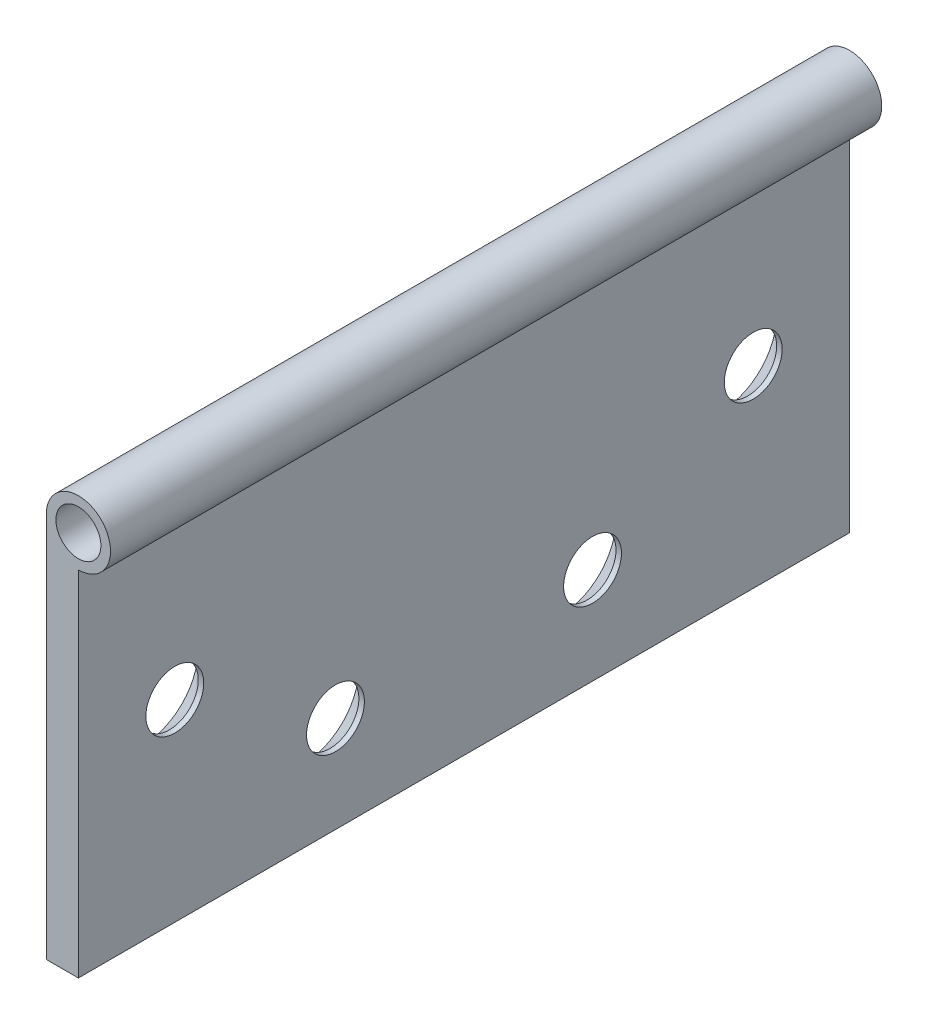
SolidWorks part; units mm, degrees
ref_plane "Спереди" through (0, 0, 0) normal (0, 0, 1) x (1, 0, 0)
ref_plane "Сверху" through (0, 0, 0) normal (0, 1, 0) x (1, 0, 0)
ref_plane "Справа" through (0, 0, 0) normal (1, 0, 0) x (0, 0, -1)
sketch "Эскиз1" plane through (0, 0, 0) normal (0, 0, 1) x (1, 0, 0)
  line L0 (0, 0) -> (0, 60)
  dimension "D1" = 60
extrude "Вытянуть-Тонкостенный2" add sketch "Эскиз1" along normal mid plane 120 thin contours L0
sketch "Эскиз2" plane through (0, 0, 60) normal (0, 0, 1) x (1, 0, 0)
  circle A0 centre (5, 60) radius 5
sweep "По траектории1" add profiles "Эскиз2" path edge at (0, 60, 0)
sketch "Эскиз3" plane through (0, 0, 60) normal (0, 0, 1) x (1, 0, 0)
  circle A0 centre (5, 60) radius 3.5
  dimension "D1" = 7
extrude "Вырез-Вытянуть1" cut sketch "Эскиз3" against normal through all
hole_wizard "Зенковка для  винта с плоской головкой M81" positions "Эскиз4" profile "Эскиз5" countersink size "M8" standard "Ansi Metric" end condition through all
sketch "Эскиз4" plane through (0, 0, 0) normal (1, 0, 0) x (0, 0, -1)
  line L0 (-60, 0) -> (-60, 55) construction
  line L1 (-60, 0) -> (60, 0) construction
  point P0 (-45, 30)
  point P2 (-20, 15)
  dimension "D1" = 15
  dimension "D2" = 15
  dimension "D3" = 30
  dimension "D4" = 40
sketch "Эскиз5" plane through (0, 30, 45) normal (0, 1, 0) x (0, 0, 1)
  line L0 (0, 0) -> (0, 10)
  line L1 (0, 10) -> (4.5, 10)
  line L2 (4.5, 10) -> (4.5, 4.15)
  line L3 (4.5, 4.15) -> (8.65, 0)
  line L5 (8.65, 0) -> (0, 0)
  line L6 (-4.5, 4.15) -> (-8.65, 0) construction
  line L11 (0, -6.35) -> (0, 107.95) construction
  dimension "Диаметр сквозного отверстия" = 9
  dimension "Глубина сквозного отверстия" = 10
  dimension "Диаметр передней зенковки" = 17.3
  dimension "Угол передней зенковки" = 90
mirror "Зеркальное отражение4" about plane through (0, 0, 0) normal (0, 0, 1) of "Зенковка для  винта с плоской головкой M81"
sketch "layout for cuts" plane through (5, 0, 0) normal (1, 0, 0) x (0, 0, -1)
  line L0 (60, 60) -> (60, 65) construction
  line L1 (60, 55) -> (60, 60) construction
  line L2 (-60, 54) -> (60, 54)
  line L3 (-60, 54) -> (60, 54)
  line L4 (-60, 65) -> (-60, 60) construction
  line L5 (-60, 60) -> (-60, 55) construction
  line L6 (60, 60) -> (60, 65)
  line L7 (60, 54) -> (60, 65)
  line L8 (-60, 65) -> (-60, 60)
  line L9 (-60, 60) -> (-60, 54)
  line L10 (-60, 65) -> (60, 65)
  line L11 (-36, 54) -> (-36, 65)
  line L12 (-12, 54) -> (-12, 65)
  line L14 (0, 0) -> (0, 65) construction
  line L15 (12, 54) -> (12, 65)
  line L16 (36, 54) -> (36, 65)
  dimension "D2" = 24
  dimension "D3" = 24
  dimension "D1" = 1
equation "\"depth\"= 5"
equation "\"width\" = 60"
equation "\"length\"= 120"
equation "\"D1@Вытянуть-Тонкостенный2\"= \"length\""
equation "\"D1@Эскиз1\"= \"width\""
equation "\"D5@Вытянуть-Тонкостенный2\"= \"depth\""
equation "\"D1@Эскиз3\"= \"depth\" / 5 * 7"
equation "\"D1@Эскиз4\"= \"width\" / 4"
equation "\"D2@Эскиз4\"= \"width\" / 4"
equation "\"D3@Эскиз4\"= \"width\" / 2"
equation "\"D4@Эскиз4\"= \"length\" / 3"
equation "\"D2@layout for cuts\"= \"length\" / 5"
equation "\"D3@layout for cuts\"= \"length\" / 5"
